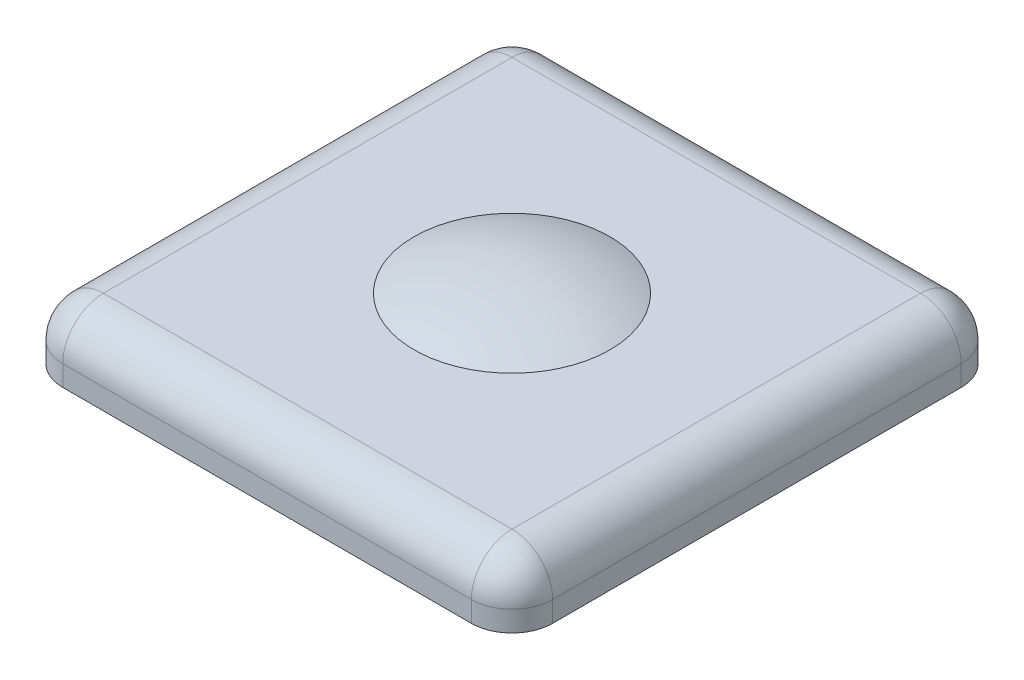
SolidWorks part; units mm, degrees
ref_plane "Front Plane" through (0, 0, 0) normal (0, 0, 1) x (1, 0, 0)
ref_plane "Top Plane" through (0, 0, 0) normal (0, 1, 0) x (1, 0, 0)
ref_plane "Right Plane" through (0, 0, 0) normal (1, 0, 0) x (0, 0, -1)
sketch "Sketch1" plane through (0, 0, 0) normal (0, 1, 0) x (1, 0, 0)
  line L0 (-12.7, 0) -> (12.7, 0) construction
  line L1 (0, -3.2639) -> (0, 3.2639) construction
  line L2 (-3.175, 12.7) -> (3.175, 12.7) construction
  line L3 (0, 12.7) -> (0, 10.5918) construction
  point P4 (0, 0)
  point P8 (0, 0)
  point P11 (0, 12.7)
  dimension "D3" = 25.4
sketch "Sketch2" plane through (0, 0, 0) normal (0, 0, 1) x (1, 0, 0)
  line L0 (0, -7.0485) -> (0, 7.0485) construction
  line L2 (5.08, 5.9954) -> (-5.08, 5.9954) construction
  line L3 (3.048, -7.0485) -> (-3.048, -7.0485) construction
  line L4 (1.6002, 0) -> (-1.6002, 0) construction
  line L5 (-3.175, 0) -> (3.175, 0) construction
  point P0 (0, 2.8204)
  point P3 (0, 0)
  point P9 (0, 5.9954)
  point P10 (0, -7.0485)
  point P11 (0, -7.0485)
  point P17 (0, 0)
  dimension "OAL" = 14.097
  dimension "Head Height" = 1.0531
  dimension "Cap Thickness" = 3.175
  dimension "Rivet Head Dea" = 10.16
  dimension "Rivet Dia" = 3.2004
  dimension "Rivet Flange Dia" = 6.096
sketch "Sketch3" plane through (0, 0, 0) normal (0, 1, 0) x (1, 0, 0)
  line L1 (12.7, -12.7) -> (-12.7, -12.7)
  line L2 (12.7, -12.7) -> (12.7, 12.7)
  line L3 (12.7, 12.7) -> (-12.7, 12.7)
  line L4 (-12.7, -12.7) -> (-12.7, 12.7)
  line L5 (12.7, -12.7) -> (-12.7, 12.7) construction
  line L6 (12.7, 12.7) -> (-12.7, -12.7) construction
  circle A0 centre (0, 0) radius 3.2639
  point P0 (0, 0)
extrude "Boss-Extrude1" add sketch "Sketch3" against normal up to vertex (-2.8204 mm away) from vertex at 5.9954 starting at point (0, 5.9954, 0)
sketch "Sketch4" plane through (0, 2.8204, 0) normal (0, -1, 0) x (1, 0, 0)
  line L1 (-3.175, -12.7) -> (3.175, -12.7)
  line L2 (-3.175, -12.7) -> (-3.175, -10.5918)
  line L3 (-3.175, -10.5918) -> (3.175, -10.5918)
  line L4 (3.175, -12.7) -> (3.175, -10.5918)
extrude "Boss-Extrude2" add sketch "Sketch4" along normal blind 2.1082
fillet "Fillet1" radius 2.1082 8 edges at (-12.7, 5.9954, 0) (0, 5.9954, -12.7) (12.7, 5.9954, 0) (0, 5.9954, 12.7) (12.7, 4.4079, 12.7) (12.7, 4.4079, -12.7) (-12.7, 4.4079, -12.7) (-12.7, 4.4079, 12.7)
sketch "Sketch5" plane through (0, 0, 0) normal (0, 0, 1) x (1, 0, 0)
  line L0 (0, -7.0485) -> (0, 7.0485) construction
  line L1 (0, -7.0485) -> (0, 7.0485) construction
  line L2 (-5.08, 5.9954) -> (-1.6002, 5.9954)
  line L3 (5.08, 5.9954) -> (-5.08, 5.9954) construction
  line L4 (-1.6002, 5.9954) -> (-1.6002, 2.3966)
  line L5 (-1.6002, 2.3966) -> (-3.048, 2.9535)
  line L6 (-3.048, 2.9535) -> (-1.6002, 1.422)
  line L7 (-1.6002, 1.422) -> (-1.6002, 2.3966) construction
  line L8 (-1.6002, 1.422) -> (-1.6002, 0.914)
  line L9 (-1.6002, 0.914) -> (-3.048, 1.4709)
  line L10 (-3.048, 1.4709) -> (-1.6002, -0.0606)
  line L11 (-1.6002, -0.0606) -> (-1.6002, -0.5686)
  line L12 (-1.6002, -0.5686) -> (-3.048, -0.0117)
  line L13 (-3.048, -0.0117) -> (-1.6002, -1.5433)
  line L14 (-1.6002, -1.5433) -> (-1.6002, -2.0513)
  line L15 (-1.6002, -2.0513) -> (-3.048, -1.4943)
  line L16 (-3.048, -1.4943) -> (-1.6002, -3.0259)
  line L17 (-1.6002, -3.0259) -> (-1.6002, -3.5339)
  line L18 (-1.6002, -3.5339) -> (-3.048, -2.977)
  line L19 (-3.048, -2.977) -> (-1.6002, -4.5085)
  line L20 (-1.6002, -4.5085) -> (-1.6002, -5.0165) construction
  line L21 (-1.6002, -4.5085) -> (-3.048, -4.5085)
  line L22 (-3.048, -4.5085) -> (-1.6589, -6.0579)
  line L23 (-1.6589, -6.0579) -> (-1.6589, -6.3881)
  line L24 (-1.6589, -6.3881) -> (-1.7859, -6.3881)
  line L25 (-1.7859, -6.3881) -> (-1.1938, -7.0485)
  line L26 (3.048, -7.0485) -> (-3.048, -7.0485) construction
  line L27 (-1.1938, -7.0485) -> (0, -7.0485)
  line L28 (0, -7.0485) -> (0, 7.0485)
  arc A0 (-5.08, 5.9954) -> (0, 7.0485) centre (0, -5.7308) cw
  dimension "D6" = 0.6604
  dimension "D7" = 2.3876
  dimension "D8" = 0.127
  dimension "D9" = 1.8796
  dimension "D10" = 0.3302
  dimension "D2" = 0.508
  dimension "D3" = 25.57
  dimension "D4" = 111.04
  dimension "D11" = 5
revolve "Revolve1" add sketch "Sketch5" angle 360 about L0
sketch "Sketch6" plane through (0, 5.9954, 0) normal (0, -1, 0) x (1, 0, 0)
  line L0 (0, 0) -> (0, 5.08) construction
  line L1 (1.6463, 5.08) -> (-1.6463, 5.08)
  line L2 (-1.6463, 5.08) -> (-0.635, 1.4688)
  line L3 (1.6463, 5.08) -> (0.635, 1.4688)
  circle A0 centre (0, 0) radius 5.08 construction
  circle A1 centre (0, 0) radius 1.6002 construction
  arc A2 (0.635, 1.4688) -> (-0.635, 1.4688) centre (0, 0) ccw
  dimension "D1" = 1.27
  dimension "D2" = 31.29
extrude "Cut-Extrude1" cut sketch "Sketch6" along normal up to surface (12.3835 mm away) up to face at (1.7859, -6.3881, 0)
equation "\"D3@Sketch1\"=\"Cap Width@Sketch1\""
equation "\"D1@Boss-Extrude2\"=\"D2@Sketch1\""
equation "\"D1@Fillet1\"=\"D2@Sketch1\""
equation "\"D10@Sketch5\"=\"D6@Sketch5\"/2"
